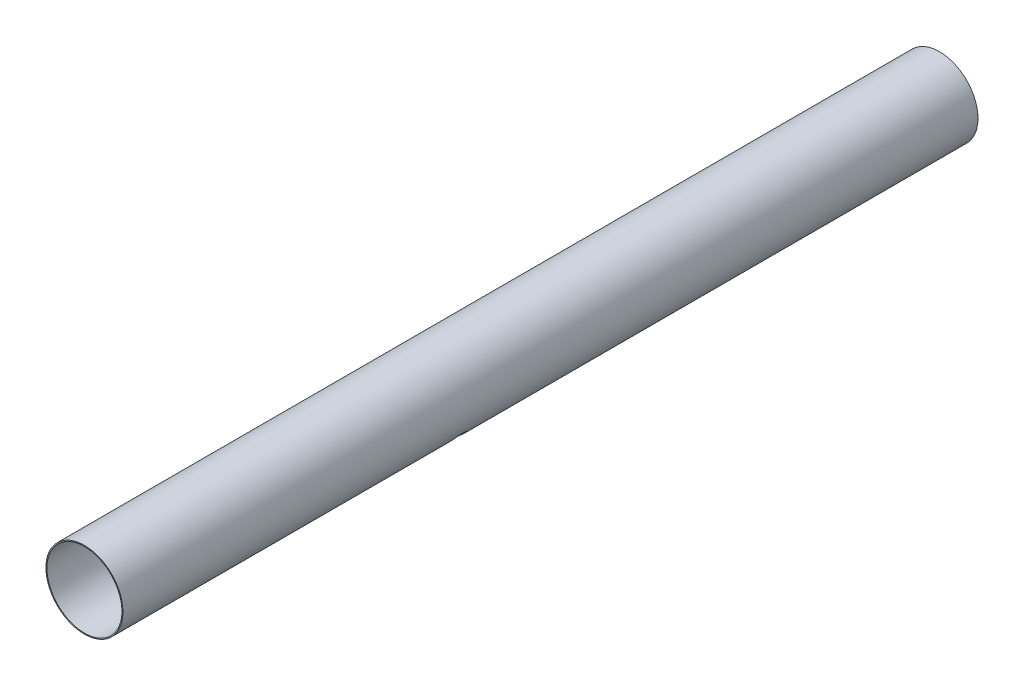
SolidWorks part; units mm, degrees
material "E-Glass Fiber"
ref_plane "Front" through (0, 0, 0) normal (0, 0, 1) x (1, 0, 0)
ref_plane "Top" through (0, 0, 0) normal (0, 1, 0) x (1, 0, 0)
ref_plane "Right" through (0, 0, 0) normal (1, 0, 0) x (0, 0, -1)
sketch "Sketch1" plane through (0, 0, 0) normal (0, 0, 1) x (1, 0, 0)
  circle A0 centre (0, 0) radius 78.35
  circle A1 centre (0, 0) radius 76.35
  dimension "D1" = 2
  dimension "D2" = 152.7
extrude "Boss-Extrude1" add sketch "Sketch1" along normal blind 1740
sketch "Sketch4" plane through (0, 0, 0) normal (0, 0, 1) x (1, 0, 0)
  line L0 (0, 0) -> (25.0476, -25.0476) construction
  line L1 (0, 0) -> (0, -24.8691) construction
  dimension "D1" = 45
ref_plane "Plane1" through (0, 0, 0) normal (0.7071, -0.7071, 0) x (0, 0, -1)
sketch "Sketch5" plane through (0, 0, 0) normal (0.7071, -0.7071, 0) x (0, 0, -1)
  line L0 (0, -78.35) -> (0, 78.35) construction
  circle A0 centre (-1034.89, 0) radius 15
  dimension "D1" = 30
  dimension "D2" = 1034.89
extrude "Cut-Extrude2" cut sketch "Sketch5" along normal through all
